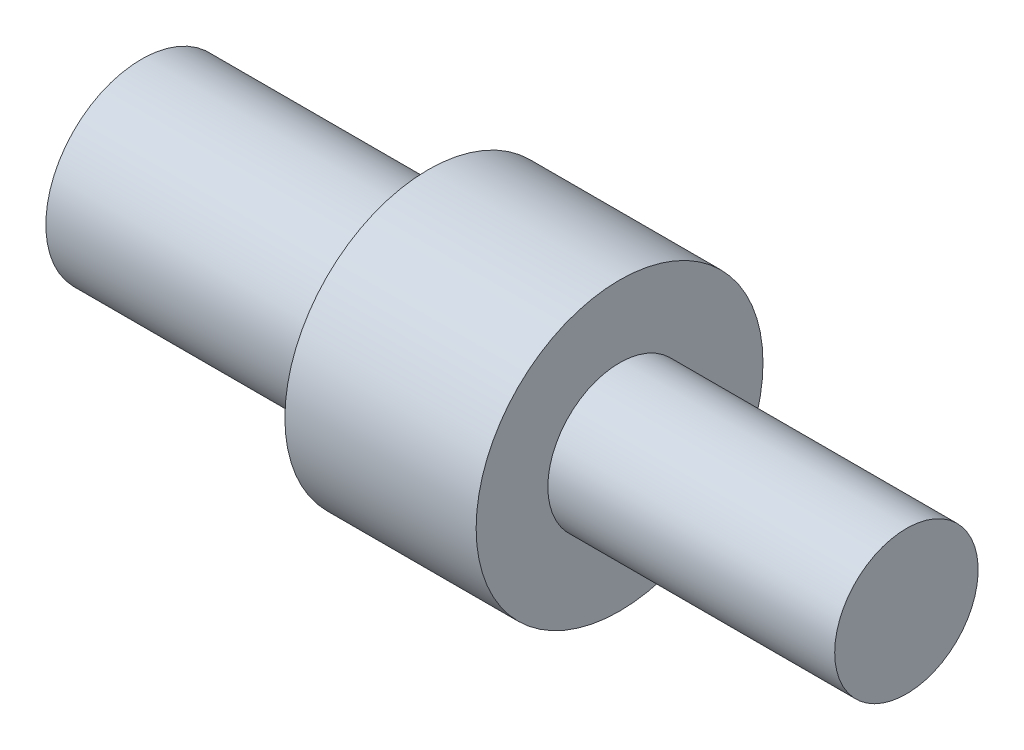
SolidWorks part; units mm, degrees
material "6061-T6 (SS)"
ref_plane "Front Plane" through (0, 0, 0) normal (0, 0, 1) x (1, 0, 0)
ref_plane "Top Plane" through (0, 0, 0) normal (0, 1, 0) x (1, 0, 0)
ref_plane "Right Plane" through (0, 0, 0) normal (1, 0, 0) x (0, 0, -1)
sketch "Sketch1" plane through (0, 0, 0) normal (1, 0, 0) x (0, 0, -1)
  circle A0 centre (0, 0) radius 9.525
  dimension "D1" = 19.05
extrude "Boss-Extrude1" add sketch "Sketch1" along normal mid plane 12.7
sketch "Sketch2" plane through (6.35, 0, 0) normal (1, 0, 0) x (0, 0, -1)
  circle A0 centre (0, 0) radius 4.7625
  dimension "D1" = 9.525
extrude "Boss-Extrude2" add sketch "Sketch2" along normal blind 19.05
sketch "Sketch3" plane through (-6.35, 0, 0) normal (-1, 0, 0) x (0, 0, 1)
  circle A0 centre (0, 0) radius 6.35
  dimension "D1" = 12.7
extrude "Boss-Extrude3" add sketch "Sketch3" along normal blind 19.05
